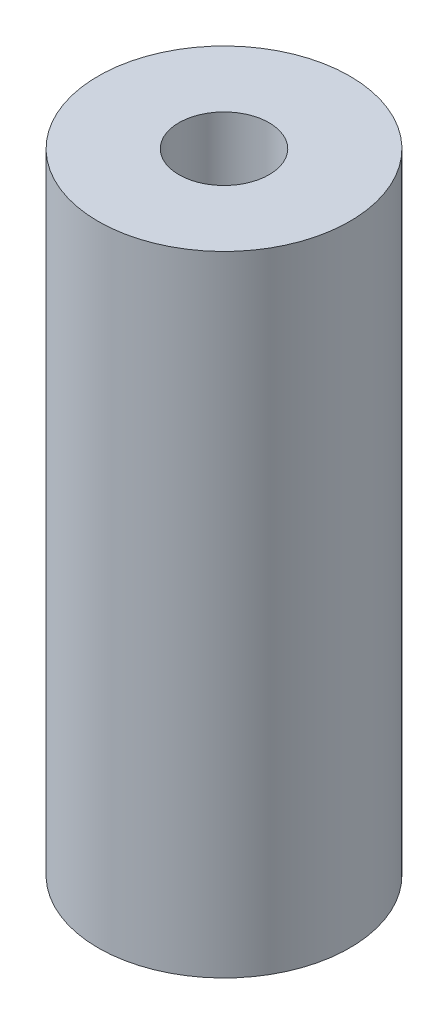
SolidWorks part; units mm, degrees
ref_plane "Спереди" through (0, 0, 0) normal (0, 0, 1) x (1, 0, 0)
ref_plane "Сверху" through (0, 0, 0) normal (0, 1, 0) x (1, 0, 0)
ref_plane "Справа" through (0, 0, 0) normal (1, 0, 0) x (0, 0, -1)
sketch "Эскиз1" plane through (0, 0, 0) normal (0, 1, 0) x (1, 0, 0)
  circle A0 centre (0, 0) radius 6
  circle A1 centre (0, 0) radius 2.15
  dimension "D1" = 4.3
  dimension "D2" = 12
extrude "Бобышка-Вытянуть1" add sketch "Эскиз1" along normal blind 30
